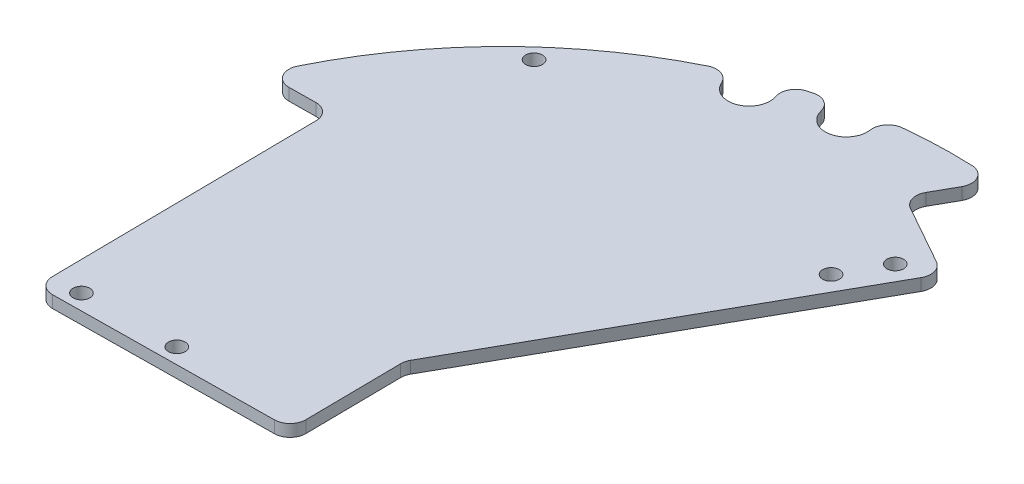
SolidWorks part; units mm, degrees
ref_plane "Front Plane" through (0, 0, 0) normal (0, 0, 1) x (1, 0, 0)
ref_plane "Top Plane" through (0, 0, 0) normal (0, 1, 0) x (1, 0, 0)
ref_plane "Right Plane" through (0, 0, 0) normal (1, 0, 0) x (0, 0, -1)
other "Configuration Table"
sketch "Sketch1" plane through (0, 0, 0) normal (0, 1, 0) x (1, 0, 0)
  line L0 (-55.6335, 61.5948) -> (-57.6443, 63.8211)
  line L1 (18.816, 65.1322) -> (2.2515, 74.4391)
  line L2 (2.2515, 74.4391) -> (8.5099, 85.5779)
  line L3 (18.816, 65.1322) -> (-18.1111, -0.591)
  line L4 (-18.1111, -0.591) -> (-17.8523, -22.7104)
  line L5 (-17.8523, -22.7104) -> (-65.7323, -23.2705)
  line L6 (-65.7323, -23.2705) -> (-66.3991, 33.7256)
  line L7 (-66.3991, 33.7256) -> (-79.1748, 33.5761)
  circle A0 centre (12.6346, 62.2966) radius 1.6
  circle A1 centre (8.2261, 54.4503) radius 1.6
  circle A2 centre (-42.269, -19.9958) radius 1.6
  circle A3 centre (-60.2677, -20.2064) radius 1.6
  circle A4 centre (-55.6335, 61.5948) radius 1.6
  circle A5 centre (0, 0) radius 86 construction
  arc A6 (8.5099, 85.5779) -> (-79.1748, 33.5761) centre (0, 0) ccw
extrude "Boss-Extrude1" add sketch "Sketch1" along normal blind 2.3
fillet "Fillet1" radius 3 8 edges at (8.5099, 1.15, -85.5779) (2.2515, 1.15, -74.4391) (18.816, 1.15, -65.1322) (-18.1111, 1.15, 0.591) (-17.8523, 1.15, 22.7104) (-65.7323, 1.15, 23.2705) (-66.3991, 1.15, -33.7256) (-79.1748, 1.15, -33.5761)
sketch "Sketch2" plane through (0, 2.3, 0) normal (0, 1, 0) x (1, 0, 0)
  point P0 (-74.4792, 36.6312)
  circle B0 centre (-30.2572, 77.2884) radius 1.6
  circle B1 centre (-15.8726, 81.4682) radius 1.6
  arc B2 (3.7063, 85.9201) -> (-77.1712, 37.9553) centre (0, 0) ccw
sketch_block_instance "Block9-1"
sketch_block "Block9"
sketch "Sketch3" plane through (0, 2.3, 0) normal (0, 1, 0) x (1, 0, 0)
  circle A0 centre (-30.2572, 77.2884) radius 4
  circle A1 centre (-15.8726, 81.4682) radius 4
  dimension "D1" = 8
extrude "Cut-Extrude1" cut sketch "Sketch3" against normal blind 44.3
fillet "Fillet2" radius 3 4 edges at (-19.0813, 1.15, -83.8564) (-13.7951, 1.15, -84.8864) (-33.843, 1.15, -79.0611) (-28.828, 1.15, -81.0244)
